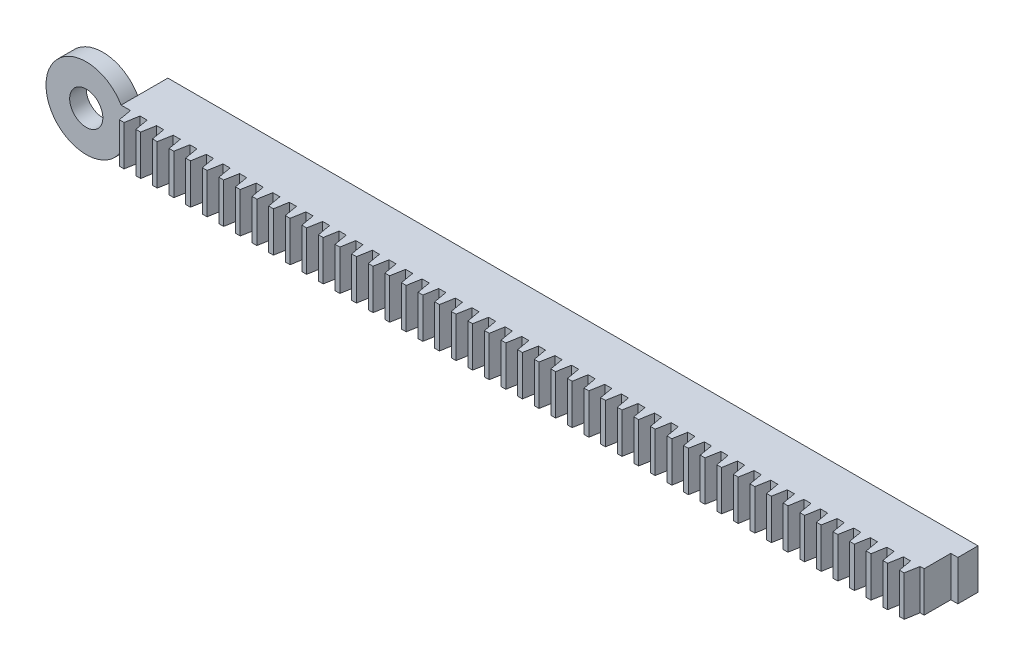
SolidWorks part; units mm, degrees
ref_plane "Front Plane" through (0, 0, 0) normal (0, 0, 1) x (1, 0, 0)
ref_plane "Top Plane" through (0, 0, 0) normal (0, 1, 0) x (1, 0, 0)
ref_plane "Right Plane" through (0, 0, 0) normal (1, 0, 0) x (0, 0, -1)
sketch "Sketch1" plane through (0, 0, 0) normal (0, 0, 1) x (1, 0, 0)
  line L1 (-11.7412, 3.0088) -> (68.2588, 3.0088)
  line L2 (-11.7412, 3.0088) -> (-11.7412, -0.9912)
  line L3 (-11.7412, -0.9912) -> (68.2588, -0.9912)
  line L4 (68.2588, 3.0088) -> (68.2588, -0.9912)
  dimension "D1" = 4
  dimension "D2" = 80
extrude "Boss-Extrude1" add sketch "Sketch1" along normal blind 2
sketch "Sketch4" plane through (0, 3.0088, 0) normal (0, 1, 0) x (1, 0, 0)
  line L0 (-11.7412, -4.65) -> (68.2588, -4.65) construction
  line L1 (-11.7412, -2) -> (-11.7412, 0) construction
  line L2 (68.2588, -2) -> (68.2588, 0) construction
  line L3 (-11.3412, -4.65) -> (-11.1031, -6)
  line L5 (-11.1031, -6) -> (-10.6331, -6)
  line L6 (-10.6331, -6) -> (-10.3951, -4.65)
  line L7 (-10.8681, -6) -> (-10.8681, -2.2401) construction
  line L8 (-11.3412, -4.65) -> (-11.7412, -4.65)
  line L9 (-10.3951, -4.65) -> (-9.9951, -4.65)
  line L10 (-11.7412, -4.65) -> (-11.7412, 0)
  line L11 (68.2588, 0) -> (-11.7412, 0) construction
  line L12 (-11.7412, 0) -> (-9.9951, 0)
  line L13 (-9.9951, 0) -> (-9.9951, -4.65)
  dimension "D1" = 0.47
  dimension "D2" = 1.35
  dimension "D3" = 0.9461
  dimension "D4" = 0.4
  dimension "D5" = 6
extrude "Boss-Extrude2" add sketch "Sketch4" against normal up to surface (4 mm away) up to face at (28.2588, -0.9912, 1)
pattern_linear "LPattern1" count 48 spacing 1.65 along (1, 0, 0) of "Boss-Extrude2"
sketch "Sketch5" plane through (0, 0, 0) normal (0, 0, 1) x (1, 0, 0)
  line L1 (-11.3412, -0.9912) -> (-11.7412, -0.9912) construction
  line L2 (-11.7412, 3.0088) -> (-12.2771, 3.0088)
  line L3 (-11.7412, 3.0088) -> (-11.7412, -0.9912)
  line L4 (-11.7412, -0.9912) -> (-12.2771, -0.9912)
  arc A2 (-12.2771, 3.0088) -> (-12.2771, -0.9912) centre (-15.7412, 1.0088) ccw
  circle A3 centre (-15.7412, 1.0088) radius 1.65
  dimension "D2" = 4
  dimension "D3" = 3.3
  dimension "D1" = 4
extrude "Boss-Extrude3" add sketch "Sketch5" along normal up to surface (4.65 mm away) up to face at (-11.5412, 1.0088, 4.65)
sketch "Sketch6" plane through (0, 3.0088, 0) normal (0, 1, 0) x (1, 0, 0)
  line L0 (-19.7412, 0) -> (-19.7412, -4.65) construction
  line L1 (-12.2771, 0) -> (-19.7412, 0)
  line L2 (-12.2771, 0) -> (-12.2771, -3)
  line L3 (-12.2771, -3) -> (-19.7412, -3)
  line L4 (-19.7412, 0) -> (-19.7412, -3)
  dimension "D1" = 3
extrude "Cut-Extrude1" cut sketch "Sketch6" against normal through all both and the other way through all
